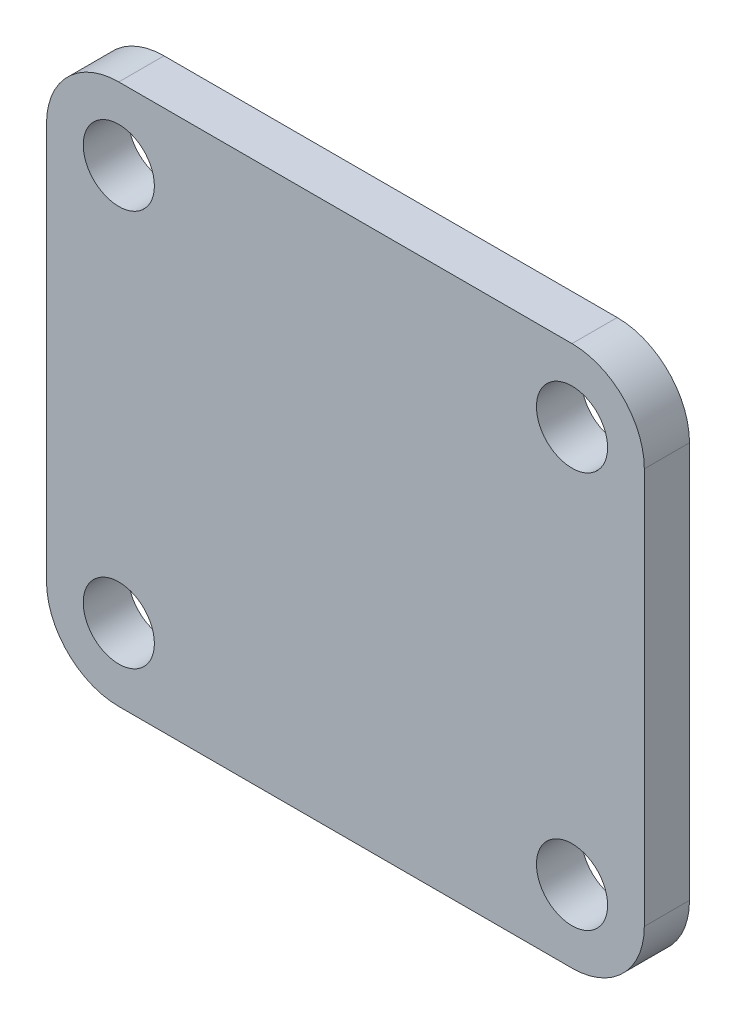
SolidWorks part; units mm, degrees
ref_plane "Plane1" through (0, 0, 0) normal (0, 0, 1) x (1, 0, 0)
ref_plane "Plane2" through (0, 0, 0) normal (0, 1, 0) x (1, 0, 0)
ref_plane "Plane3" through (0, 0, 0) normal (1, 0, 0) x (0, 0, -1)
sketch "Sketch1" plane through (0, 0, 0) normal (0, 0, 1) x (1, 0, 0)
  line L1 (7.96, -9.5) -> (-7.96, -9.5)
  line L2 (10.5, -6.96) -> (10.5, 6.96)
  line L3 (7.96, 9.5) -> (-7.96, 9.5)
  line L4 (-10.5, -6.96) -> (-10.5, 6.96)
  line L5 (10.5, -9.5) -> (-10.5, 9.5) construction
  line L6 (10.5, 9.5) -> (-10.5, -9.5) construction
  arc A0 (-7.96, -9.5) -> (-10.5, -6.96) centre (-7.96, -6.96) cw
  arc A1 (7.96, -9.5) -> (10.5, -6.96) centre (7.96, -6.96) ccw
  arc A2 (10.5, 6.96) -> (7.96, 9.5) centre (7.96, 6.96) ccw
  arc A3 (-7.96, 9.5) -> (-10.5, 6.96) centre (-7.96, 6.96) ccw
  point P0 (0, 0)
  dimension "D3" = 2.54
  dimension "D1" = 21
  dimension "D2" = 19
extrude "Boss-Extrude1" add sketch "Sketch1" along normal blind 1.5875
sketch "Sketch2" plane through (0, 0, 1.5875) normal (0, 0, 1) x (1, 0, 0)
  circle A0 centre (-7.96, 6.96) radius 1.25
  circle A1 centre (7.96, 6.96) radius 1.25
  circle A2 centre (7.96, -6.96) radius 1.25
  circle A3 centre (-7.96, -6.96) radius 1.25
  dimension "D1" = 2.5
extrude "Cut-Extrude1" cut sketch "Sketch2" against normal through all
